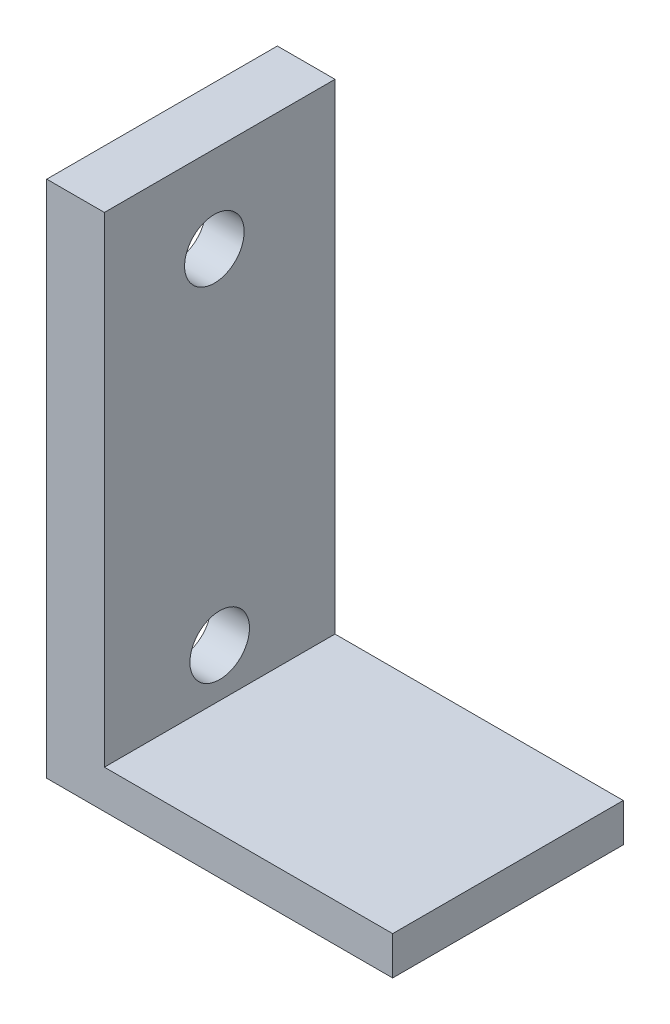
SolidWorks part; units mm, degrees
ref_plane "Plan de face" through (0, 0, 0) normal (0, 0, 1) x (1, 0, 0)
ref_plane "Plan de dessus" through (0, 0, 0) normal (0, 1, 0) x (1, 0, 0)
ref_plane "Plan de droite" through (0, 0, 0) normal (1, 0, 0) x (0, 0, -1)
sketch "Sketch1" plane through (0, 0, 0) normal (0, 0, 1) x (1, 0, 0)
  line L0 (0, 13.037) -> (-3, 13.037)
  line L1 (-3, 13.037) -> (-3, -13.963)
  line L2 (-3, -13.963) -> (15, -13.963)
  line L3 (15, -13.963) -> (15, -11.963)
  line L4 (15, -11.963) -> (0, -11.963)
  line L5 (0, -11.963) -> (0, 13.037)
  dimension "D1" = 25
  dimension "D2" = 2
  dimension "D3" = 27
  dimension "D4" = 3
  dimension "D5" = 18
extrude "Boss-Extrude1" add sketch "Sketch1" along normal blind 12
ref_plane "Plane1" through (-3, 0, 0) normal (-1, 0, 0) x (0, 0, 1)
sketch "Sketch2" plane through (-3, 0, 0) normal (-1, 0, 0) x (0, 0, 1)
  line L0 (12, -13.963) -> (0, -13.963) construction
  circle A0 centre (6.0554, -9.463) radius 3.5
  circle A1 centre (6.277, 8.537) radius 3.5
  point P4 (0, 0)
  dimension "D1" = 18
  dimension "D2" = 4.5
extrude "Cut-Extrude1" cut sketch "Sketch2" against normal blind 1
sketch "Sketch3" plane through (-3, 0, 0) normal (-1, 0, 0) x (0, 0, 1)
  circle A1 centre (6.277, 8.537) radius 1.55
  circle A2 centre (6.0554, -9.463) radius 1.55
  point P6 (0, 0)
  point P7 (0, 0)
  point P9 (0, 0)
  dimension "D1" = 3.1
  dimension "D2" = 3.1
  dimension "D3" = 18
extrude "Cut-Extrude2" cut sketch "Sketch3" against normal blind 3.1 contours A1
sketch "Sketch5" plane through (0, 0, 0) normal (1, 0, 0) x (0, 0, -1)
  line L0 (-12, -11.963) -> (-12, 13.037) construction
  circle A0 centre (-6, -9.463) radius 1.55
  circle A1 centre (-6.277, 8.537) radius 1.55 construction
  dimension "D1" = 3.1
  dimension "D3" = 3.1
  dimension "D2" = 18
  dimension "D4" = 6
extrude "Cut-Extrude3" cut sketch "Sketch5" against normal blind 11
